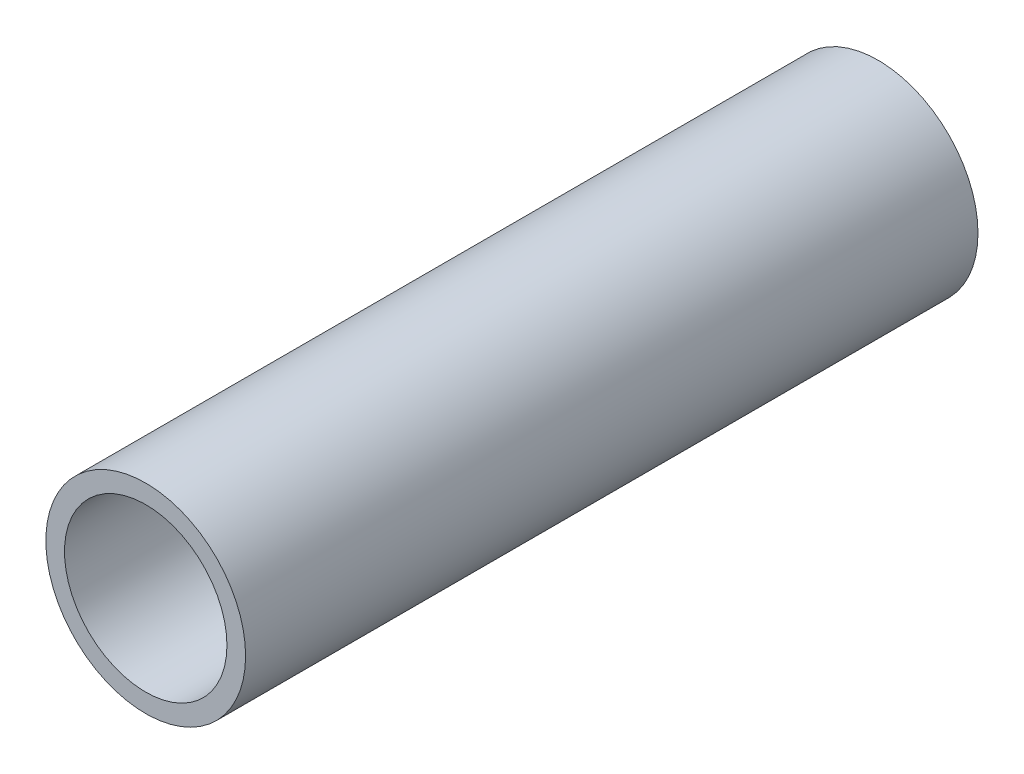
SolidWorks part; units mm, degrees
ref_plane "정면" through (0, 0, 0) normal (0, 0, 1) x (1, 0, 0)
ref_plane "윗면" through (0, 0, 0) normal (0, 1, 0) x (1, 0, 0)
ref_plane "우측면" through (0, 0, 0) normal (1, 0, 0) x (0, 0, -1)
sketch "스케치1" plane through (0, 0, 0) normal (0, 1, 0) x (1, 0, 0)
  line L0 (7.5, 0) -> (6.1, 0)
  line L1 (6.1, 0) -> (6.1, -200)
  line L2 (6.1, -200) -> (7.5, -200)
  line L3 (7.5, -200) -> (7.5, 0)
  line L4 (0, 0) -> (0, -200) construction
revolve "회전1" add sketch "스케치1" angle 360 about L4
sketch "스케치2" plane through (0, 0, 200) normal (0, 0, 1) x (1, 0, 0)
  circle A1 centre (0, 0) radius 7.5
  circle A2 centre (0, 0) radius 7.5
  dimension "D1" = 0
extrude "컷-돌출1" cut sketch "스케치2" against normal blind 145
